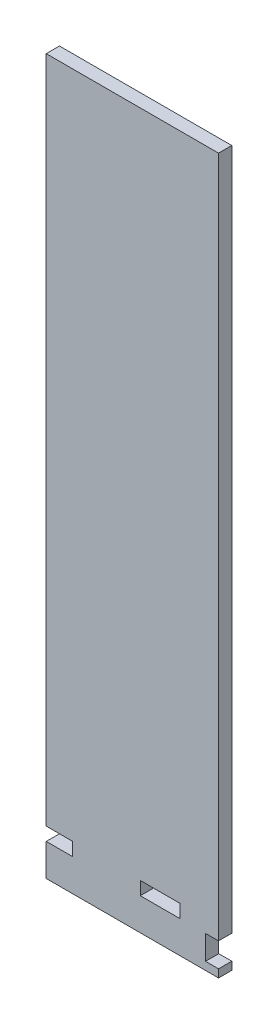
SolidWorks part; units mm, degrees
material "Balsa"
ref_plane "Plan de face" through (0, 0, 0) normal (0, 0, 1) x (1, 0, 0)
ref_plane "Plan de dessus" through (0, 0, 0) normal (0, 1, 0) x (1, 0, 0)
ref_plane "Plan de droite" through (0, 0, 0) normal (1, 0, 0) x (0, 0, -1)
sketch "Esquisse1" plane through (0, 0, 0) normal (0, 0, 1) x (1, 0, 0)
  line L1 (65.1211, 0) -> (0, 0)
  line L2 (65.1211, 0) -> (65.1211, 270)
  line L3 (65.1211, 270) -> (0, 270)
  line L4 (0, 0) -> (0, 270)
  dimension "D1" = 270
  dimension "D2" = 65.1211
extrude "Boss.-Extru.1" add sketch "Esquisse1" against normal blind 5
sketch "Esquisse2" plane through (0, 0, 0) normal (0, 0, 1) x (1, 0, 0)
  line L0 (0, 270) -> (0, 0) construction
  line L1 (0, 17.15) -> (10, 17.15)
  line L2 (0, 17.15) -> (0, 12.15)
  line L3 (0, 12.15) -> (10, 12.15)
  line L4 (10, 17.15) -> (10, 12.15)
  line L5 (65.1211, 0) -> (65.1211, 270) construction
  line L6 (50.5493, 17.15) -> (35.5493, 17.15)
  line L7 (50.5493, 17.15) -> (50.5493, 12.15)
  line L8 (50.5493, 12.15) -> (35.5493, 12.15)
  line L9 (35.5493, 17.15) -> (35.5493, 12.15)
  line L10 (65.1211, 12.15) -> (60.2011, 12.15)
  line L11 (65.1211, 12.15) -> (65.1211, 3)
  line L12 (65.1211, 3) -> (60.2011, 3)
  line L13 (60.2011, 12.15) -> (60.2011, 3)
  line L14 (0, 0) -> (65.1211, 0) construction
  dimension "D1" = 3
  dimension "D2" = 4.92
  dimension "D3" = 9.15
  dimension "D4" = 12.15
  dimension "D5" = 5
  dimension "D6" = 5
extrude "Enlèv. mat.-Extru.1" cut sketch "Esquisse2" against normal blind 5
